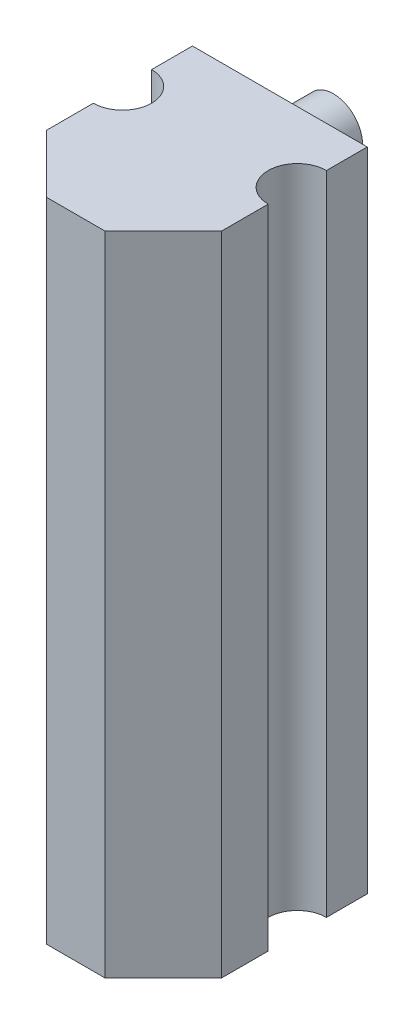
SolidWorks part; units mm, degrees
ref_plane "Front Plane" through (0, 0, 0) normal (0, 0, 1) x (1, 0, 0)
ref_plane "Top Plane" through (0, 0, 0) normal (0, 1, 0) x (1, 0, 0)
ref_plane "Right Plane" through (0, 0, 0) normal (1, 0, 0) x (0, 0, -1)
sketch "Sketch1" plane through (0, 0, 0) normal (0, 0, 1) x (1, 0, 0)
  line L1 (-14.1891, 55.5) -> (15.8109, 55.5)
  line L2 (-14.1891, 55.5) -> (-14.1891, -55.5)
  line L3 (-14.1891, -55.5) -> (15.8109, -55.5)
  line L4 (15.8109, 55.5) -> (15.8109, -55.5)
  dimension "D1" = 30
  dimension "D2" = 111
  dimension "D3" = 55.5
extrude "Boss-Extrude1" add sketch "Sketch1" along normal blind 35
sketch "Sketch2" plane through (0, 55.5, 0) normal (0, 1, 0) x (1, 0, 0)
  line L0 (0.8109, -35) -> (0.8109, -11.9849) construction
  line L1 (15.8109, -35) -> (-14.1891, -35) construction
  line L2 (5.8109, -35) -> (15.8109, -25)
  line L3 (15.8109, -35) -> (15.8109, 0) construction
  line L4 (15.8109, -25) -> (15.8109, -35)
  line L5 (15.8109, -35) -> (5.8109, -35)
  line L6 (15.8109, 0) -> (-14.1891, 0) construction
  line L7 (15.8109, -7) -> (15.8109, -17)
  line L8 (-14.1891, -25) -> (-14.1891, -35)
  line L9 (-14.1891, -35) -> (-4.1891, -35)
  line L10 (-4.1891, -35) -> (-14.1891, -25)
  line L11 (-14.1891, -7) -> (-14.1891, -17)
  arc A0 (15.8109, -7) -> (15.8109, -17) centre (15.8109, -12) ccw
  arc A1 (-14.1891, -7) -> (-14.1891, -17) centre (-14.1891, -12) cw
  dimension "D3" = 12
  dimension "D4" = 5
  dimension "D1" = 5
  dimension "D2" = 10
extrude "Cut-Extrude1" cut sketch "Sketch2" against normal through all
sketch "Sketch3" plane through (0, 0, 0) normal (0, 0, -1) x (-1, 0, 0)
  line L0 (0, 0) -> (0, 45.5) construction
  circle A0 centre (0, 45.5) radius 5
  circle A1 centre (0, -45.5) radius 5
  dimension "D1" = 91
  dimension "D2" = 45.5
extrude "Boss-Extrude2" add sketch "Sketch3" along normal blind 10
